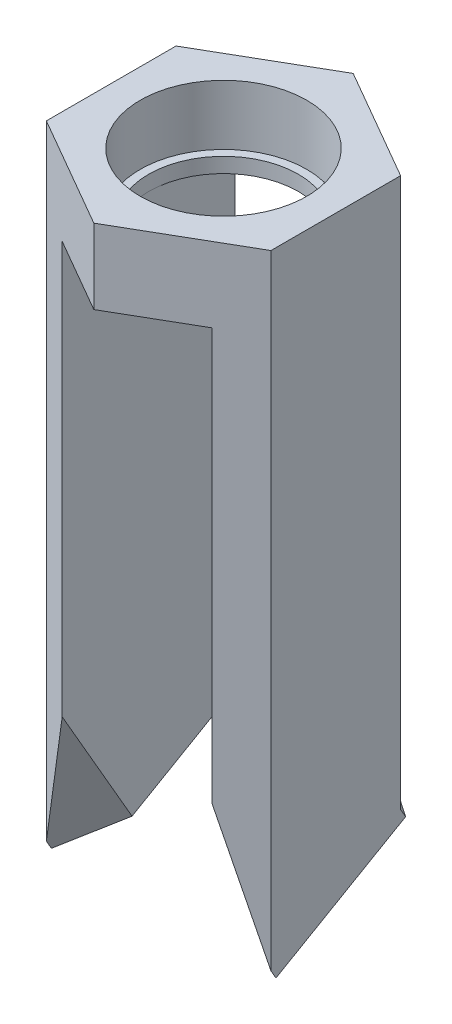
SolidWorks part; units mm, degrees
ref_plane "Front Plane" through (0, 0, 0) normal (0, 0, 1) x (1, 0, 0)
ref_plane "Top Plane" through (0, 0, 0) normal (0, 1, 0) x (1, 0, 0)
ref_plane "Right Plane" through (0, 0, 0) normal (1, 0, 0) x (0, 0, -1)
sketch "Sketch2" plane through (0, 0, 0) normal (0, 1, 0) x (1, 0, 0)
  line L1 (0, 17.3205) -> (-15, 8.6603)
  line L2 (-15, 8.6603) -> (-15, -8.6603)
  line L3 (-15, -8.6603) -> (0, -17.3205)
  line L4 (0, -17.3205) -> (15, -8.6603)
  line L5 (15, -8.6603) -> (15, 8.6603)
  line L6 (15, 8.6603) -> (0, 17.3205)
  circle A0 centre (0, 0) radius 15 construction
  circle A1 centre (0, 0) radius 11.125
  dimension "D2" = 22.25
  dimension "D1" = 30
extrude "Boss-Extrude1" add sketch "Sketch2" along normal blind 8
sketch "Sketch3" plane through (0, 0, 0) normal (0, -1, 0) x (1, 0, 0)
  line L0 (15, 8.6603) -> (15, -8.6603) construction
  line L1 (0, 17.3205) -> (-15, 8.6603)
  line L2 (-15, 8.6603) -> (-15, -8.6603)
  line L3 (-15, -8.6603) -> (0, -17.3205)
  line L4 (0, -17.3205) -> (15, -8.6603)
  line L5 (15, -8.6603) -> (15, 8.6603)
  line L6 (15, 8.6603) -> (0, 17.3205)
  circle A0 centre (0, 0) radius 15 construction
  circle A1 centre (0, 0) radius 10
  dimension "D1" = 20
extrude "Boss-Extrude2" add sketch "Sketch3" along normal blind 2
sketch "Sketch4" plane through (0, -2, 0) normal (0, -1, 0) x (1, 0, 0)
  line L0 (0, 17.3205) -> (-15, 8.6603) construction
  line L1 (-10, 11.547) -> (-15, 8.6603)
  line L2 (-15, 8.6603) -> (-15, -8.6603)
  line L3 (-15, -8.6603) -> (-10, -11.547)
  line L4 (10, -11.547) -> (15, -8.6603)
  line L5 (15, -8.6603) -> (15, 8.6603)
  line L6 (15, 8.6603) -> (10, 11.547)
  line L7 (-10, -11.547) -> (-10, 11.547)
  line L8 (10, 11.547) -> (10, -11.547)
  line L9 (0, 17.3205) -> (-7.5, 12.9904) construction
  line L10 (7.5, 12.9904) -> (0, 17.3205) construction
  line L11 (0, -17.3205) -> (7.5, -12.9904) construction
  line L12 (-7.5, -12.9904) -> (0, -17.3205) construction
  line L13 (-10, -11.547) -> (-7.5, -12.9904) construction
  line L14 (7.5, -12.9904) -> (10, -11.547) construction
  line L15 (10, 11.547) -> (7.5, 12.9904) construction
  line L16 (-7.5, 12.9904) -> (-10, 11.547) construction
  arc A0 (-10, 11.1803) -> (-10, -11.1803) centre (0, 0) ccw construction
  circle A1 centre (0, 0) radius 10 construction
  arc A2 (7.5, 12.9904) -> (-7.5, 12.9904) centre (0, 0) ccw construction
  arc A3 (-7.5, -12.9904) -> (7.5, -12.9904) centre (0, 0) ccw construction
  arc A4 (10, -11.1803) -> (10, 11.1803) centre (0, 0) ccw construction
  arc A5 (-10, -11.1803) -> (-7.5, -12.9904) centre (0, 0) ccw construction
  arc A6 (7.5, -12.9904) -> (10, -11.1803) centre (0, 0) ccw construction
  arc A7 (10, 11.1803) -> (7.5, 12.9904) centre (0, 0) ccw construction
  arc A8 (-7.5, 12.9904) -> (-10, 11.1803) centre (0, 0) ccw construction
extrude "Boss-Extrude3" add sketch "Sketch4" along normal blind 75
sketch "Sketch5" plane through (-15, 0, 0) normal (-1, 0, 0) x (0, 0, 1)
  line L0 (-8.6603, -77) -> (-45.4663, -55.75) construction
  line L1 (-45.4663, -55.75) -> (-8.6603, 8) construction
  line L2 (-8.6603, 8) -> (-8.6603, -77) construction
  line L3 (11.547, -77) -> (-11.547, -63.6667)
  line L4 (-11.547, -77) -> (-11.547, -2) construction
  line L5 (-11.547, -63.6667) -> (-11.547, -77)
  line L6 (-11.547, -77) -> (11.547, -77)
  dimension "D1" = 90
  dimension "D2" = 30
extrude "Cut-Extrude1" cut sketch "Sketch5" against normal through all
sketch "Sketch6" plane through (0, -52.75, -30.4552) normal (0, -0.866, -0.5) x (1, 0, 0)
  line L0 (-10, 48.5) -> (-15, 45.1667)
  line L1 (-15, 45.1667) -> (-15, 25.1667)
  line L2 (-15, 25.1667) -> (-10, 21.8333)
  line L3 (-10, 21.8333) -> (-10, 48.5)
  line L4 (10, 48.5) -> (15, 45.1667)
  line L5 (15, 45.1667) -> (15, 25.1667)
  line L6 (15, 25.1667) -> (10, 21.8333)
  line L7 (10, 21.8333) -> (10, 48.5)
extrude "Boss-Extrude4" add sketch "Sketch6" along normal blind 1.34
sketch "Sketch9" plane through (0, -53.9105, -31.1252) normal (0, -0.866, -0.5) x (1, 0, 0)
  line L0 (-15, 45.1667) -> (-10, 38.5)
  line L1 (-10, 21.8333) -> (-10, 48.5) construction
  line L2 (-10, 38.5) -> (-10, 48.5)
  line L3 (-10, 48.5) -> (-15, 45.1667)
  line L4 (10, 48.5) -> (10, 38.5)
  line L5 (10, 48.5) -> (10, 21.8333) construction
  line L6 (10, 38.5) -> (15, 45.1667)
  line L7 (15, 45.1667) -> (10, 48.5) construction
  line L8 (15, 45.1667) -> (10, 48.5)
  point P15 (13.1881, 58.8746)
  point P16 (15.0124, 57.6667)
  point P17 (14.9986, 57.6667)
  point P18 (14.9325, 57.7117)
  dimension "D1" = 10
  dimension "D2" = 10
extrude "Cut-Extrude4" cut sketch "Sketch9" against normal through all
sketch "Sketch14" plane through (0, -53.9105, -31.1252) normal (0, -0.866, -0.5) x (1, 0, 0)
  circle A0 centre (-12.4986, 34.7322) radius 1.5
  circle A1 centre (-12.4986, 27.5803) radius 1.5
  circle A2 centre (12.4986, 27.5803) radius 1.5
  circle A3 centre (12.4986, 37.1481) radius 1.5
extrude "Cut-Extrude6" cut sketch "Sketch14" against normal blind 10
sketch "Sketch16" plane through (-15, 0, 0) normal (-1, 0, 0) x (0, 0, 1)
  line L0 (11.547, -2) -> (5.547, -2)
  line L1 (8.6603, 8) -> (8.6603, -75.3333) construction
  dimension "D1" = 6
  dimension "D2" = 2.8868
